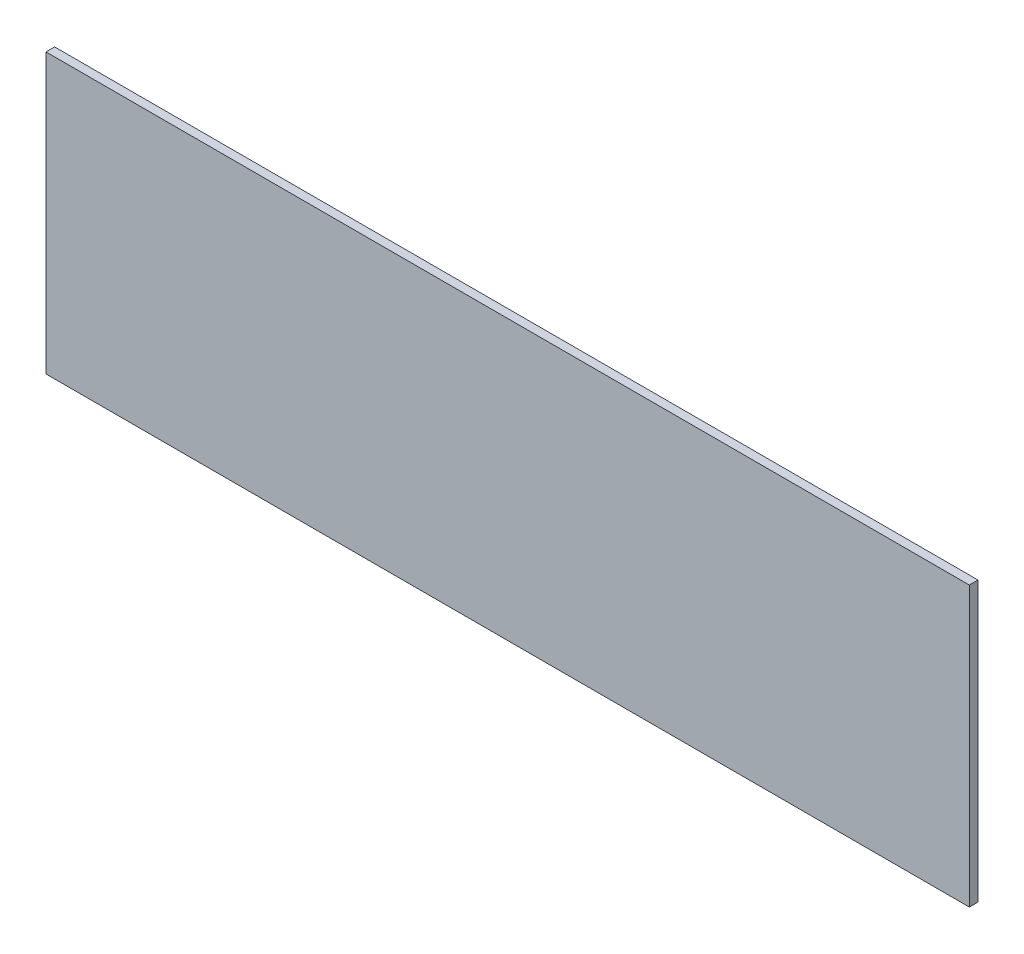
SolidWorks part; units mm, degrees
material "Custom Plastic"
ref_plane "Front Plane" through (0, 0, 0) normal (0, 0, 1) x (1, 0, 0)
ref_plane "Top Plane" through (0, 0, 0) normal (0, 1, 0) x (1, 0, 0)
ref_plane "Right Plane" through (0, 0, 0) normal (1, 0, 0) x (0, 0, -1)
sketch "Sketch1" plane through (0, 0, 0) normal (0, 0, 1) x (1, 0, 0)
  line L1 (-480, -145) -> (480, -145)
  line L2 (-480, -145) -> (-480, 145)
  line L3 (-480, 145) -> (480, 145)
  line L4 (480, -145) -> (480, 145)
  line L5 (-480, -145) -> (480, 145) construction
  line L6 (-480, 145) -> (480, -145) construction
  point P0 (0, 0)
extrude "Boss-Extrude1" add sketch "Sketch1" along normal blind 9
